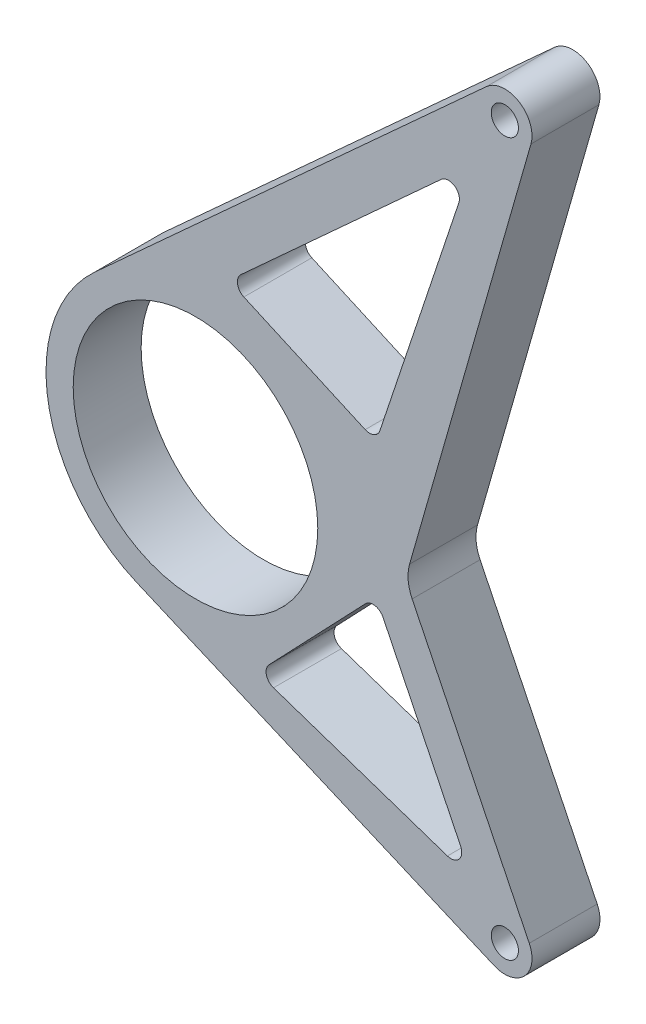
SolidWorks part; units mm, degrees
material "1023 Carbon Steel Sheet (SS)"
ref_plane "Front Plane" through (0, 0, 0) normal (0, 0, 1) x (1, 0, 0)
ref_plane "Top Plane" through (0, 0, 0) normal (0, 1, 0) x (1, 0, 0)
ref_plane "Right Plane" through (0, 0, 0) normal (1, 0, 0) x (0, 0, -1)
sketch "Sketch2" plane through (0, 0, 0) normal (0, 0, 1) x (1, 0, 0)
  line L0 (-38.6653, 39.1784) -> (107.0992, 171.8423)
  line L1 (-21.6474, -50.5608) -> (109.8942, -106.8797)
  line L2 (122.8143, -93.2954) -> (79.7177, -5.1262)
  line L3 (78.7806, 5.486) -> (123.4448, 161.6976)
  line L4 (113.8301, 164.4467) -> (-141.4394, 164.4467) construction
  line L5 (113.8301, -97.6868) -> (-130.107, -97.6868) construction
  line L6 (0, 0) -> (113.8301, 164.4467) construction
  line L7 (0, 0) -> (113.8301, -97.6868) construction
  circle A0 centre (0, 0) radius 45
  arc A1 (-37.02, 40.6758) -> (-21.6474, -50.5608) centre (0, 0) ccw
  circle A2 centre (113.8301, 164.4467) radius 5
  arc A3 (123.4448, 161.6976) -> (107.0992, 171.8423) centre (113.8301, 164.4467) ccw
  arc A4 (109.8942, -106.8797) -> (122.8143, -93.2954) centre (113.8301, -97.6868) ccw
  circle A5 centre (113.8301, -97.6868) radius 5
  arc A6 (79.7177, -5.1262) -> (78.7806, 5.486) centre (93.0701, 1.4003) cw
  point P23 (77.2121, 0)
  dimension "D1" = 90
  dimension "D2" = 10
  dimension "D3" = 20
  dimension "D4" = 20
  dimension "D5" = 10
  dimension "D9" = 110
  dimension "D10" = 14.8621
  dimension "D6" = 200
  dimension "D7" = 55.309
  dimension "D8" = 150
extrude "Boss-Extrude2" add sketch "Sketch2" along normal blind 25 contours L2 A6 L3 A3 L0 A1 L1 A4 A0 A2 A5
sketch "Sketch3" plane through (0, 0, 25) normal (0, 0, 1) x (1, 0, 0)
  line L0 (17.7957, 60.1214) -> (62.4379, 40.1841)
  line L1 (67.8638, 42.5715) -> (96.9029, 129.6889)
  line L2 (90.4131, 133.9096) -> (16.7318, 66.7296)
  line L3 (27.0859, -52.4066) -> (62.4963, -15.2896)
  line L4 (68.9868, -16.2997) -> (97.5712, -75.0068)
  line L5 (92.6961, -80.5479) -> (28.7014, -58.9578)
  arc A0 (27.0859, -52.4066) -> (28.7014, -58.9578) centre (29.9801, -55.1677) ccw
  arc A1 (68.9868, -16.2997) -> (62.4963, -15.2896) centre (65.3905, -18.0507) ccw
  arc A2 (92.6961, -80.5479) -> (97.5712, -75.0068) centre (93.9748, -76.7578) ccw
  arc A3 (62.4379, 40.1841) -> (67.8638, 42.5715) centre (64.0691, 43.8365) ccw
  arc A4 (16.7318, 66.7296) -> (17.7957, 60.1214) centre (19.4269, 63.7738) ccw
  arc A5 (90.4131, 133.9096) -> (96.9029, 129.6889) centre (93.1082, 130.9538) cw
  dimension "D1" = 4
extrude "Cut-Extrude1" cut sketch "Sketch3" against normal up to surface (25 mm away) up to face at (45, 0, 0)
